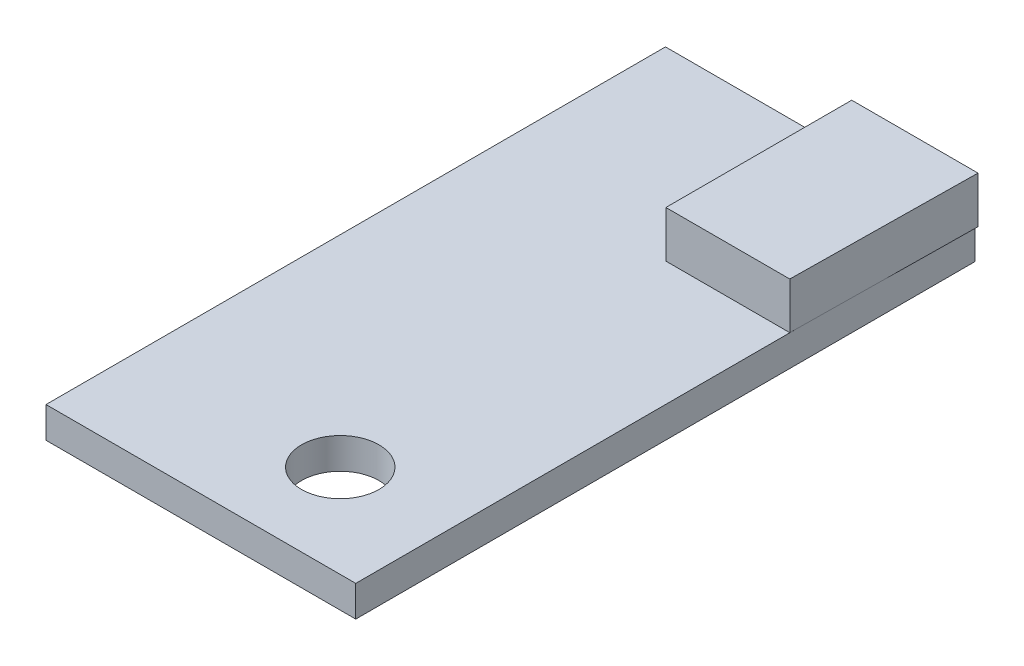
SolidWorks part; units mm, degrees
ref_plane "Front Plane" through (0, 0, 0) normal (0, 0, 1) x (1, 0, 0)
ref_plane "Top Plane" through (0, 0, 0) normal (0, 1, 0) x (1, 0, 0)
ref_plane "Right Plane" through (0, 0, 0) normal (1, 0, 0) x (0, 0, -1)
sketch "Sketch2" plane through (0, 0, 0) normal (0, 1, 0) x (1, 0, 0)
  line L0 (0, 0) -> (100, 0)
  line L1 (0, 0) -> (0, -200)
  line L2 (100, 0) -> (100, -200)
  line L3 (100, -200) -> (0, -200)
  dimension "D1" = 100
  dimension "D2" = 200
extrude "Boss-Extrude1" add sketch "Sketch2" along normal blind 10
sketch "Sketch3" plane through (0.8679, 10, -1.6939) normal (0, 1, 0) x (1, 0, 0)
  line L0 (59.0975, -1.5331) -> (59.0975, -61.5331)
  line L2 (59.0975, -61.5331) -> (99.0975, -61.5331)
  line L3 (99.8668, -1.5331) -> (59.0975, -1.5331)
  line L5 (99.8668, -1.5331) -> (99.0975, -61.5331)
  dimension "D1" = 40
  dimension "D2" = 60
extrude "Boss-Extrude2" add sketch "Sketch3" along normal blind 15
sketch "Sketch8" plane through (0, 10, 0) normal (0, 1, 0) x (1, 0, 0)
  point P0 (65, -170)
hole_wizard "Ø25.0mm Dowel Hole1" positions "Sketch9" profile "Sketch10" hole size "Ø25.0" standard "ANSI Metric" end condition through all
sketch "Sketch9" plane through (0, 10, 0) normal (0, 1, 0) x (1, 0, 0)
  point P0 (65, -170)
sketch "Sketch10" plane through (65, 10, 170) normal (1, 0, 0) x (0, 0, 1)
  line L0 (0, 0) -> (0, 10)
  line L1 (0, 10) -> (12.5, 10)
  line L2 (12.5, 10) -> (12.5, 0)
  line L5 (12.5, 0) -> (0, 0)
  line L11 (0, -6.35) -> (0, 107.95) construction
  dimension "Thru Hole Dia." = 25
  dimension "Thru Hole Depth" = 10
